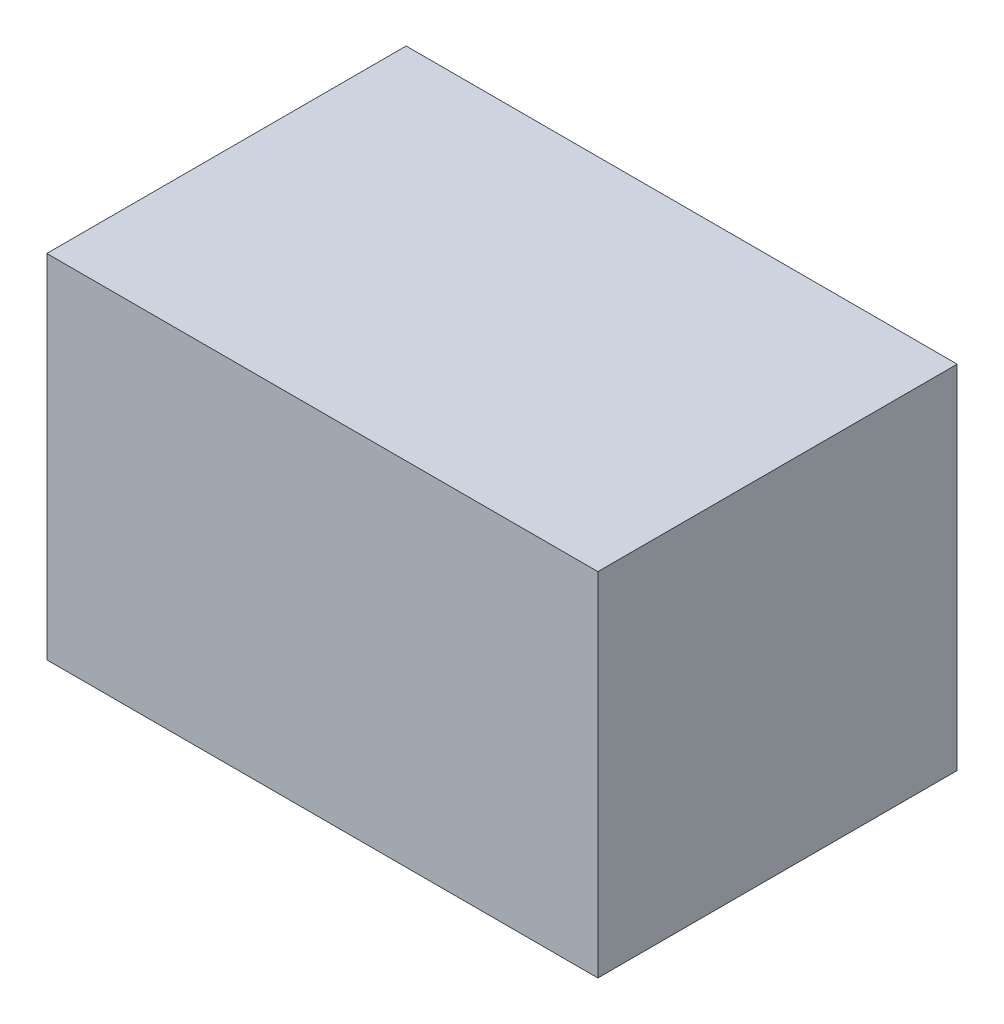
SolidWorks part; units mm, degrees
ref_plane "Front Plane" through (0, 0, 0) normal (0, 0, 1) x (1, 0, 0)
ref_plane "Top Plane" through (0, 0, 0) normal (0, 1, 0) x (1, 0, 0)
ref_plane "Right Plane" through (0, 0, 0) normal (1, 0, 0) x (0, 0, -1)
sketch "Sketch1" plane through (0, 0, 0) normal (0, 1, 0) x (1, 0, 0)
  line L1 (-75.565, 49.276) -> (75.565, 49.276)
  line L2 (-75.565, 49.276) -> (-75.565, -49.276)
  line L3 (-75.565, -49.276) -> (75.565, -49.276)
  line L4 (75.565, 49.276) -> (75.565, -49.276)
  line L5 (-75.565, 49.276) -> (75.565, -49.276) construction
  line L6 (-75.565, -49.276) -> (75.565, 49.276) construction
  point P0 (0, 0)
  dimension "D1" = 151.13
  dimension "D2" = 98.552
extrude "Boss-Extrude1" add sketch "Sketch1" along normal blind 96.52
